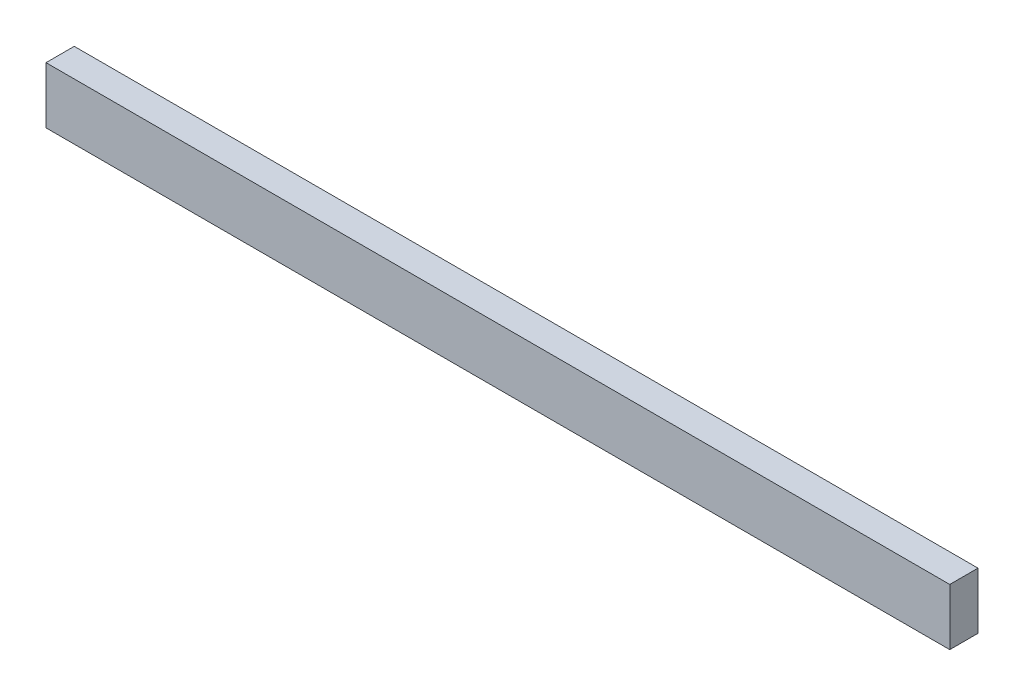
SolidWorks part; units mm, degrees
ref_plane "Front Plane" through (0, 0, 0) normal (0, 0, 1) x (1, 0, 0)
ref_plane "Top Plane" through (0, 0, 0) normal (0, 1, 0) x (1, 0, 0)
ref_plane "Right Plane" through (0, 0, 0) normal (1, 0, 0) x (0, 0, -1)
sketch "Sketch1" plane through (0, 0, 0) normal (0, 1, 0) x (1, 0, 0)
  line L1 (0, 0) -> (1219.2, 0)
  line L2 (0, 0) -> (0, 38.1)
  line L3 (0, 38.1) -> (1219.2, 38.1)
  line L4 (1219.2, 0) -> (1219.2, 38.1)
  dimension "D1" = 1219.2
  dimension "D2" = 38.1
extrude "Extrude1" add sketch "Sketch1" along normal blind 76.2
